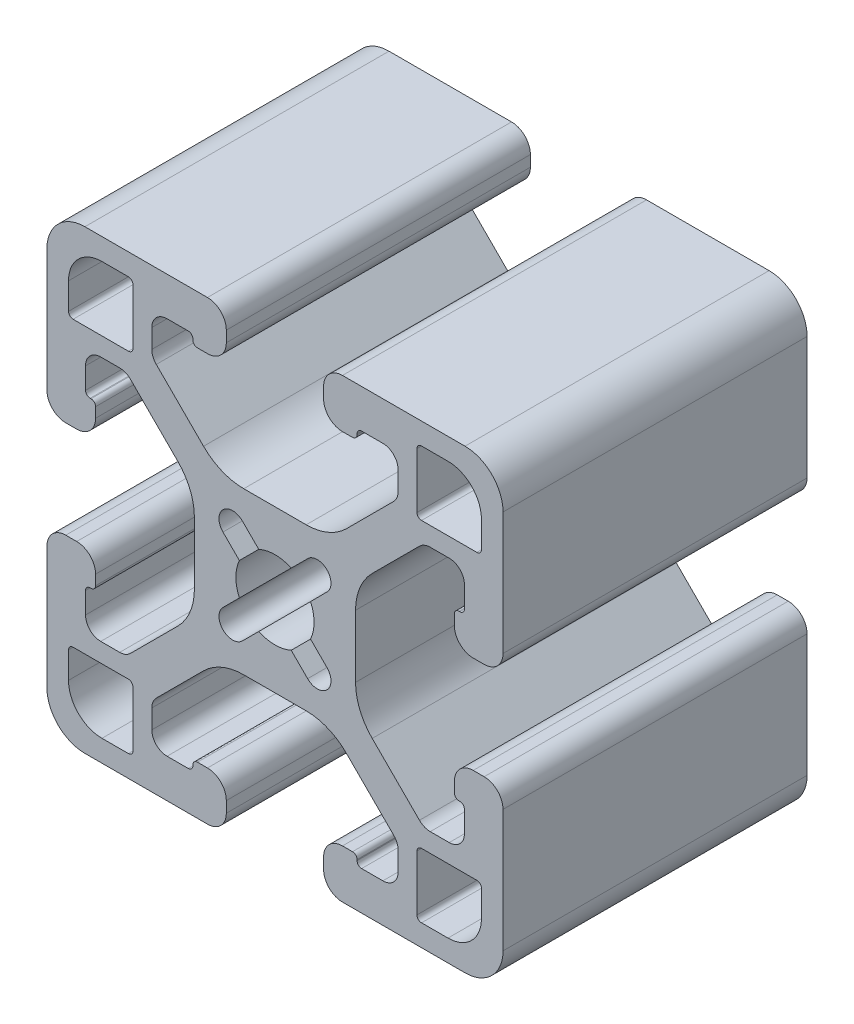
SolidWorks part; units mm, degrees
ref_plane "Front Plane" through (0, 0, 0) normal (0, 0, 1) x (1, 0, 0)
ref_plane "Top Plane" through (0, 0, 0) normal (0, 1, 0) x (1, 0, 0)
ref_plane "Right Plane" through (0, 0, 0) normal (1, 0, 0) x (0, 0, -1)
sketch "Sketch1" plane through (0, 0, 0) normal (0, 0, 1) x (1, 0, 0)
  line L0 (-66.7042, -2.4885) -> (-65.3338, -1.1181)
  line L1 (-65.3338, 1.5948) -> (-66.7042, 2.9652)
  line L2 (-65.0878, 4.5817) -> (-63.7174, 3.2113)
  line L3 (-61.0045, 3.2113) -> (-59.7212, 4.484)
  line L4 (-58.1153, 2.8781) -> (-59.3881, 1.5948)
  line L5 (-59.3881, -1.1181) -> (-58.0176, -2.4885)
  line L6 (-59.6341, -4.1049) -> (-61.0045, -2.7345)
  line L7 (-63.7174, -2.7345) -> (-65.0878, -4.1049)
  line L8 (-79.6075, 12.4812) -> (-79.6075, 14.691)
  line L9 (-76.8135, 17.485) -> (-74.6037, 17.485)
  line L10 (-74.2227, 17.104) -> (-74.2227, 12.4812)
  line L11 (-74.6037, 12.1002) -> (-79.2265, 12.1002)
  line L12 (-74.6037, -17.0082) -> (-76.8135, -17.0082)
  line L13 (-79.6075, -14.2142) -> (-79.6075, -12.0044)
  line L14 (-79.2265, -11.6234) -> (-74.6037, -11.6234)
  line L15 (-74.2227, -12.0044) -> (-74.2227, -16.6272)
  line L16 (-45.1143, -12.0044) -> (-45.1143, -14.2142)
  line L17 (-47.9083, -17.0082) -> (-50.1181, -17.0082)
  line L18 (-50.4991, -16.6272) -> (-50.4991, -12.0044)
  line L19 (-50.1181, -11.6234) -> (-45.4953, -11.6234)
  line L20 (-50.1181, 17.485) -> (-47.9083, 17.485)
  line L21 (-45.1143, 14.691) -> (-45.1143, 12.4812)
  line L22 (-45.4953, 12.1002) -> (-50.1181, 12.1002)
  line L23 (-50.4991, 12.4812) -> (-50.4991, 17.104)
  line L24 (-46.5368, -7.0006) -> (-46.5368, -8.7746)
  line L25 (-47.8067, -10.0486) -> (-49.3926, -10.0486)
  line L26 (-50.2907, -9.6767) -> (-54.2388, -5.7286)
  line L27 (-55.6299, -2.3699) -> (-55.6299, 2.8467)
  line L28 (-54.2388, 6.2053) -> (-50.2907, 10.1534)
  line L29 (-49.3926, 10.5254) -> (-47.8067, 10.5254)
  line L30 (-46.5368, 9.2513) -> (-46.5368, 7.4774)
  line L31 (-46.9178, 7.0964) -> (-46.994, 7.0964)
  line L32 (-47.375, 6.7154) -> (-47.3749, 5.8772)
  line L33 (-45.8001, 4.3024) -> (-44.8857, 4.3024)
  line L34 (-43.3109, 5.8772) -> (-43.3109, 16.1134)
  line L35 (-46.4859, 19.2884) -> (-56.7221, 19.2884)
  line L36 (-58.2969, 17.7136) -> (-58.2969, 16.7992)
  line L37 (-56.7222, 15.2244) -> (-55.884, 15.2244)
  line L38 (-55.503, 15.6054) -> (-55.503, 15.6816)
  line L39 (-55.122, 16.0626) -> (-53.348, 16.0626)
  line L40 (-52.0739, 14.7926) -> (-52.0739, 13.2067)
  line L41 (-52.4459, 12.3087) -> (-56.394, 8.3606)
  line L42 (-59.7526, 6.9694) -> (-64.9693, 6.9694)
  line L43 (-68.3279, 8.3606) -> (-72.276, 12.3087)
  line L44 (-72.6479, 13.2067) -> (-72.6479, 14.7926)
  line L45 (-71.3739, 16.0626) -> (-69.5999, 16.0626)
  line L46 (-69.2189, 15.6816) -> (-69.2189, 15.6054)
  line L47 (-68.8379, 15.2244) -> (-67.9997, 15.2244)
  line L48 (-66.4249, 16.7992) -> (-66.4249, 17.7136)
  line L49 (-67.9997, 19.2884) -> (-78.2359, 19.2884)
  line L50 (-81.4109, 16.1134) -> (-81.4109, 5.8772)
  line L51 (-79.8361, 4.3024) -> (-78.9217, 4.3024)
  line L52 (-77.3469, 5.8772) -> (-77.3469, 6.7154)
  line L53 (-77.7279, 7.0964) -> (-77.8041, 7.0964)
  line L54 (-78.1851, 7.4774) -> (-78.1851, 9.2513)
  line L55 (-76.9151, 10.5254) -> (-75.3293, 10.5254)
  line L56 (-74.4312, 10.1534) -> (-70.4831, 6.2053)
  line L57 (-69.0919, 2.8467) -> (-69.0919, -2.3699)
  line L58 (-70.4831, -5.7286) -> (-74.4312, -9.6767)
  line L59 (-75.3293, -10.0486) -> (-76.9151, -10.0486)
  line L60 (-78.1851, -8.7746) -> (-78.1851, -7.0006)
  line L61 (-77.8041, -6.6196) -> (-77.7279, -6.6196)
  line L62 (-77.3469, -6.2386) -> (-77.3469, -5.4004)
  line L63 (-78.9217, -3.8256) -> (-79.8361, -3.8256)
  line L64 (-81.4109, -5.4004) -> (-81.4109, -15.6366)
  line L65 (-78.2359, -18.8116) -> (-67.9997, -18.8116)
  line L66 (-66.4249, -17.2368) -> (-66.4249, -16.3224)
  line L67 (-67.9997, -14.7476) -> (-68.8379, -14.7476)
  line L68 (-69.2189, -15.1286) -> (-69.2189, -15.2048)
  line L69 (-69.5999, -15.5858) -> (-71.3739, -15.5858)
  line L70 (-72.6479, -14.3158) -> (-72.6479, -12.7299)
  line L71 (-72.276, -11.8319) -> (-68.3279, -7.8838)
  line L72 (-64.9693, -6.4926) -> (-59.7526, -6.4926)
  line L73 (-56.394, -7.8838) -> (-52.4459, -11.8319)
  line L74 (-52.0739, -12.7299) -> (-52.0739, -14.3158)
  line L75 (-53.348, -15.5858) -> (-55.122, -15.5858)
  line L76 (-55.503, -15.2048) -> (-55.503, -15.1286)
  line L77 (-55.884, -14.7476) -> (-56.7222, -14.7476)
  line L78 (-58.2969, -16.3224) -> (-58.2969, -17.2368)
  line L79 (-56.7221, -18.8116) -> (-46.4859, -18.8116)
  line L80 (-43.3109, -15.6366) -> (-43.3109, -5.4004)
  line L81 (-44.8857, -3.8256) -> (-45.8001, -3.8256)
  line L82 (-47.3749, -5.4004) -> (-47.375, -6.2386)
  line L83 (-46.994, -6.6196) -> (-46.9178, -6.6196)
  arc A0 (-66.7042, -2.4885) -> (-65.0878, -4.1049) centre (-65.896, -3.2967) ccw
  arc A1 (-65.3338, 1.5948) -> (-65.3338, -1.1181) centre (-62.3609, 0.2384) ccw
  arc A2 (-65.0878, 4.5817) -> (-66.7042, 2.9652) centre (-65.896, 3.7734) ccw
  arc A3 (-61.0045, 3.2113) -> (-63.7174, 3.2113) centre (-62.3609, 0.2384) ccw
  arc A4 (-58.1153, 2.8781) -> (-59.7212, 4.484) centre (-58.8259, 3.7734) ccw
  arc A5 (-59.3881, -1.1181) -> (-59.3881, 1.5948) centre (-62.3609, 0.2384) ccw
  arc A6 (-59.6341, -4.1049) -> (-58.0176, -2.4885) centre (-58.8259, -3.2967) ccw
  arc A7 (-63.7174, -2.7345) -> (-61.0045, -2.7345) centre (-62.3609, 0.2384) ccw
  arc A8 (-79.6075, 12.4812) -> (-79.2265, 12.1002) centre (-79.2265, 12.4812) ccw
  arc A9 (-76.8135, 17.485) -> (-79.6075, 14.691) centre (-76.8135, 14.691) ccw
  arc A10 (-74.2227, 17.104) -> (-74.6037, 17.485) centre (-74.6037, 17.104) ccw
  arc A11 (-74.6037, 12.1002) -> (-74.2227, 12.4812) centre (-74.6037, 12.4812) ccw
  arc A12 (-74.6037, -17.0082) -> (-74.2227, -16.6272) centre (-74.6037, -16.6272) ccw
  arc A13 (-79.6075, -14.2142) -> (-76.8135, -17.0082) centre (-76.8135, -14.2142) ccw
  arc A14 (-79.2265, -11.6234) -> (-79.6075, -12.0044) centre (-79.2265, -12.0044) ccw
  arc A15 (-74.2227, -12.0044) -> (-74.6037, -11.6234) centre (-74.6037, -12.0044) ccw
  arc A16 (-45.1143, -12.0044) -> (-45.4953, -11.6234) centre (-45.4953, -12.0044) ccw
  arc A17 (-47.9083, -17.0082) -> (-45.1143, -14.2142) centre (-47.9083, -14.2142) ccw
  arc A18 (-50.4991, -16.6272) -> (-50.1181, -17.0082) centre (-50.1181, -16.6272) ccw
  arc A19 (-50.1181, -11.6234) -> (-50.4991, -12.0044) centre (-50.1181, -12.0044) ccw
  arc A20 (-50.1181, 17.485) -> (-50.4991, 17.104) centre (-50.1181, 17.104) ccw
  arc A21 (-45.1143, 14.691) -> (-47.9083, 17.485) centre (-47.9083, 14.691) ccw
  arc A22 (-45.4953, 12.1002) -> (-45.1143, 12.4812) centre (-45.4953, 12.4812) ccw
  arc A23 (-50.4991, 12.4812) -> (-50.1181, 12.1002) centre (-50.1181, 12.4812) ccw
  arc A24 (-47.8067, -10.0486) -> (-46.5368, -8.7746) centre (-47.8067, -8.7786) ccw
  arc A25 (-50.2907, -9.6767) -> (-49.3926, -10.0486) centre (-49.3926, -8.7786) ccw
  arc A26 (-55.6299, -2.3699) -> (-54.2388, -5.7286) centre (-50.8801, -2.3699) ccw
  arc A27 (-54.2388, 6.2053) -> (-55.6299, 2.8467) centre (-50.8801, 2.8467) ccw
  arc A28 (-49.3926, 10.5254) -> (-50.2907, 10.1534) centre (-49.3926, 9.2554) ccw
  arc A29 (-46.5368, 9.2513) -> (-47.8067, 10.5254) centre (-47.8067, 9.2554) ccw
  arc A30 (-46.9178, 7.0964) -> (-46.5368, 7.4774) centre (-46.9178, 7.4774) ccw
  arc A31 (-46.994, 7.0964) -> (-47.375, 6.7154) centre (-46.994, 6.7154) ccw
  arc A32 (-47.3749, 5.8772) -> (-45.8001, 4.3024) centre (-45.8001, 5.8772) ccw
  arc A33 (-44.8857, 4.3024) -> (-43.3109, 5.8772) centre (-44.8857, 5.8772) ccw
  arc A34 (-43.3109, 16.1134) -> (-46.4859, 19.2884) centre (-46.4859, 16.1134) ccw
  arc A35 (-56.7221, 19.2884) -> (-58.2969, 17.7136) centre (-56.7221, 17.7136) ccw
  arc A36 (-58.2969, 16.7992) -> (-56.7222, 15.2244) centre (-56.7221, 16.7992) ccw
  arc A37 (-55.884, 15.2244) -> (-55.503, 15.6054) centre (-55.884, 15.6054) ccw
  arc A38 (-55.122, 16.0626) -> (-55.503, 15.6816) centre (-55.122, 15.6816) ccw
  arc A39 (-52.0739, 14.7926) -> (-53.348, 16.0626) centre (-53.3439, 14.7926) ccw
  arc A40 (-52.4459, 12.3087) -> (-52.0739, 13.2067) centre (-53.3439, 13.2067) ccw
  arc A41 (-59.7526, 6.9694) -> (-56.394, 8.3606) centre (-59.7526, 11.7192) ccw
  arc A42 (-68.3279, 8.3606) -> (-64.9693, 6.9694) centre (-64.9693, 11.7192) ccw
  arc A43 (-72.6479, 13.2067) -> (-72.276, 12.3087) centre (-71.3779, 13.2067) ccw
  arc A44 (-71.3739, 16.0626) -> (-72.6479, 14.7926) centre (-71.3779, 14.7926) ccw
  arc A45 (-69.2189, 15.6816) -> (-69.5999, 16.0626) centre (-69.5999, 15.6816) ccw
  arc A46 (-69.2189, 15.6054) -> (-68.8379, 15.2244) centre (-68.8379, 15.6054) ccw
  arc A47 (-67.9997, 15.2244) -> (-66.4249, 16.7992) centre (-67.9997, 16.7992) ccw
  arc A48 (-66.4249, 17.7136) -> (-67.9997, 19.2884) centre (-67.9997, 17.7136) ccw
  arc A49 (-78.2359, 19.2884) -> (-81.4109, 16.1134) centre (-78.2359, 16.1134) ccw
  arc A50 (-81.4109, 5.8772) -> (-79.8361, 4.3024) centre (-79.8361, 5.8772) ccw
  arc A51 (-78.9217, 4.3024) -> (-77.3469, 5.8772) centre (-78.9217, 5.8772) ccw
  arc A52 (-77.3469, 6.7154) -> (-77.7279, 7.0964) centre (-77.7279, 6.7154) ccw
  arc A53 (-78.1851, 7.4774) -> (-77.8041, 7.0964) centre (-77.8041, 7.4774) ccw
  arc A54 (-76.9151, 10.5254) -> (-78.1851, 9.2513) centre (-76.9151, 9.2554) ccw
  arc A55 (-74.4312, 10.1534) -> (-75.3293, 10.5254) centre (-75.3293, 9.2554) ccw
  arc A56 (-69.0919, 2.8467) -> (-70.4831, 6.2053) centre (-73.8417, 2.8467) ccw
  arc A57 (-70.4831, -5.7286) -> (-69.0919, -2.3699) centre (-73.8417, -2.3699) ccw
  arc A58 (-75.3293, -10.0486) -> (-74.4312, -9.6767) centre (-75.3293, -8.7786) ccw
  arc A59 (-78.1851, -8.7746) -> (-76.9151, -10.0486) centre (-76.9151, -8.7786) ccw
  arc A60 (-77.8041, -6.6196) -> (-78.1851, -7.0006) centre (-77.8041, -7.0006) ccw
  arc A61 (-77.7279, -6.6196) -> (-77.3469, -6.2386) centre (-77.7279, -6.2386) ccw
  arc A62 (-77.3469, -5.4004) -> (-78.9217, -3.8256) centre (-78.9217, -5.4004) ccw
  arc A63 (-79.8361, -3.8256) -> (-81.4109, -5.4004) centre (-79.8361, -5.4004) ccw
  arc A64 (-81.4109, -15.6366) -> (-78.2359, -18.8116) centre (-78.2359, -15.6366) ccw
  arc A65 (-67.9997, -18.8116) -> (-66.4249, -17.2368) centre (-67.9997, -17.2368) ccw
  arc A66 (-66.4249, -16.3224) -> (-67.9997, -14.7476) centre (-67.9997, -16.3224) ccw
  arc A67 (-68.8379, -14.7476) -> (-69.2189, -15.1286) centre (-68.8379, -15.1286) ccw
  arc A68 (-69.5999, -15.5858) -> (-69.2189, -15.2048) centre (-69.5999, -15.2048) ccw
  arc A69 (-72.6479, -14.3158) -> (-71.3739, -15.5858) centre (-71.3779, -14.3158) ccw
  arc A70 (-72.276, -11.8319) -> (-72.6479, -12.7299) centre (-71.3779, -12.7299) ccw
  arc A71 (-64.9693, -6.4926) -> (-68.3279, -7.8838) centre (-64.9693, -11.2424) ccw
  arc A72 (-56.394, -7.8838) -> (-59.7526, -6.4926) centre (-59.7526, -11.2424) ccw
  arc A73 (-52.0739, -12.7299) -> (-52.4459, -11.8319) centre (-53.3439, -12.7299) ccw
  arc A74 (-53.348, -15.5858) -> (-52.0739, -14.3158) centre (-53.3439, -14.3158) ccw
  arc A75 (-55.503, -15.2048) -> (-55.122, -15.5858) centre (-55.122, -15.2048) ccw
  arc A76 (-55.503, -15.1286) -> (-55.884, -14.7476) centre (-55.884, -15.1286) ccw
  arc A77 (-56.7222, -14.7476) -> (-58.2969, -16.3224) centre (-56.7221, -16.3224) ccw
  arc A78 (-58.2969, -17.2368) -> (-56.7221, -18.8116) centre (-56.7221, -17.2368) ccw
  arc A79 (-46.4859, -18.8116) -> (-43.3109, -15.6366) centre (-46.4859, -15.6366) ccw
  arc A80 (-43.3109, -5.4004) -> (-44.8857, -3.8256) centre (-44.8857, -5.4004) ccw
  arc A81 (-45.8001, -3.8256) -> (-47.3749, -5.4004) centre (-45.8001, -5.4004) ccw
  arc A82 (-47.375, -6.2386) -> (-46.994, -6.6196) centre (-46.994, -6.2386) ccw
  arc A83 (-46.5368, -7.0006) -> (-46.9178, -6.6196) centre (-46.9178, -7.0006) ccw
extrude "Extrude1" add sketch "Sketch1" against normal blind 25.4
